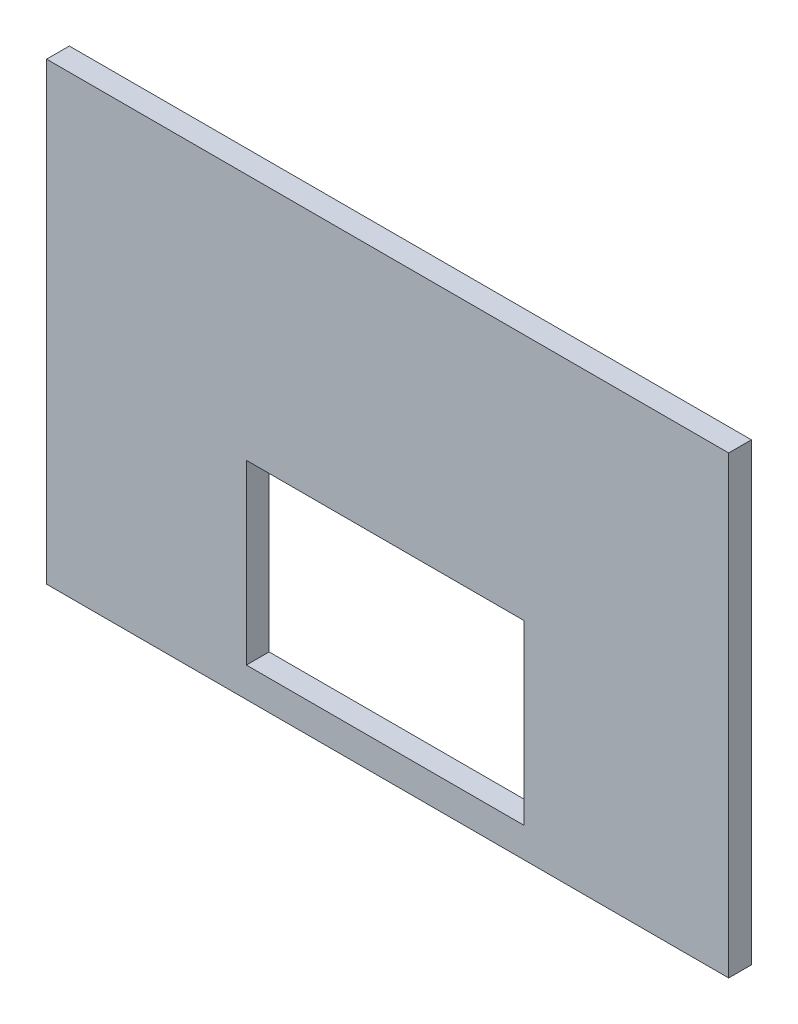
SolidWorks part; units mm, degrees
ref_plane "Front Plane" through (0, 0, 0) normal (0, 0, 1) x (1, 0, 0)
ref_plane "Top Plane" through (0, 0, 0) normal (0, 1, 0) x (1, 0, 0)
ref_plane "Right Plane" through (0, 0, 0) normal (1, 0, 0) x (0, 0, -1)
sketch "Sketch1" plane through (0, 0, 0) normal (0, 0, 1) x (1, 0, 0)
  line L1 (-54.4304, -68.6709) -> (245.5696, -68.6709)
  line L2 (-54.4304, -68.6709) -> (-54.4304, 131.3291)
  line L3 (-54.4304, 131.3291) -> (245.5696, 131.3291)
  line L4 (245.5696, -68.6709) -> (245.5696, 131.3291)
  line L5 (33.443, -55.5316) -> (155.443, -55.5316)
  line L6 (33.443, -55.5316) -> (33.443, 22.4684)
  line L7 (33.443, 22.4684) -> (155.443, 22.4684)
  line L8 (155.443, -55.5316) -> (155.443, 22.4684)
  dimension "D1" = 300
  dimension "D2" = 200
  dimension "D3" = 122
  dimension "D4" = 78
extrude "Boss-Extrude1" add sketch "Sketch1" along normal blind 10
